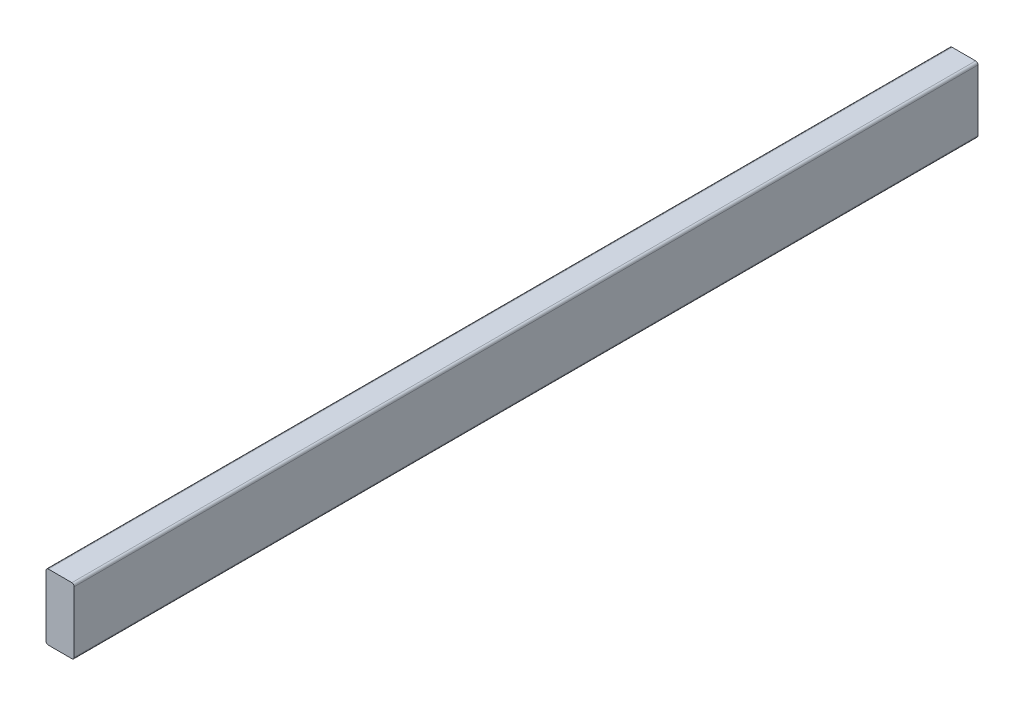
SolidWorks part; units mm, degrees
material "Pine"
ref_plane "Front Plane" through (0, 0, 0) normal (0, 0, 1) x (1, 0, 0)
ref_plane "Top Plane" through (0, 0, 0) normal (0, 1, 0) x (1, 0, 0)
ref_plane "Right Plane" through (0, 0, 0) normal (1, 0, 0) x (0, 0, -1)
sketch "Sketch1" plane through (0, 0, 0) normal (0, 0, 1) x (1, 0, 0)
  line L1 (-19.05, -44.45) -> (19.05, -44.45)
  line L2 (-19.05, -44.45) -> (-19.05, 44.45)
  line L3 (-19.05, 44.45) -> (19.05, 44.45)
  line L4 (19.05, -44.45) -> (19.05, 44.45)
  line L5 (-19.05, -44.45) -> (19.05, 44.45) construction
  line L6 (-19.05, 44.45) -> (19.05, -44.45) construction
  point P0 (0, 0)
  dimension "D1" = 38.1
  dimension "D2" = 88.9
extrude "Boss-Extrude1" add sketch "Sketch1" along normal blind 1219.2
fillet "Fillet1" radius 3.175 4 edges at (-19.05, -44.45, 609.6) (19.05, -44.45, 609.6) (-19.05, 44.45, 609.6) (19.05, 44.45, 609.6)
